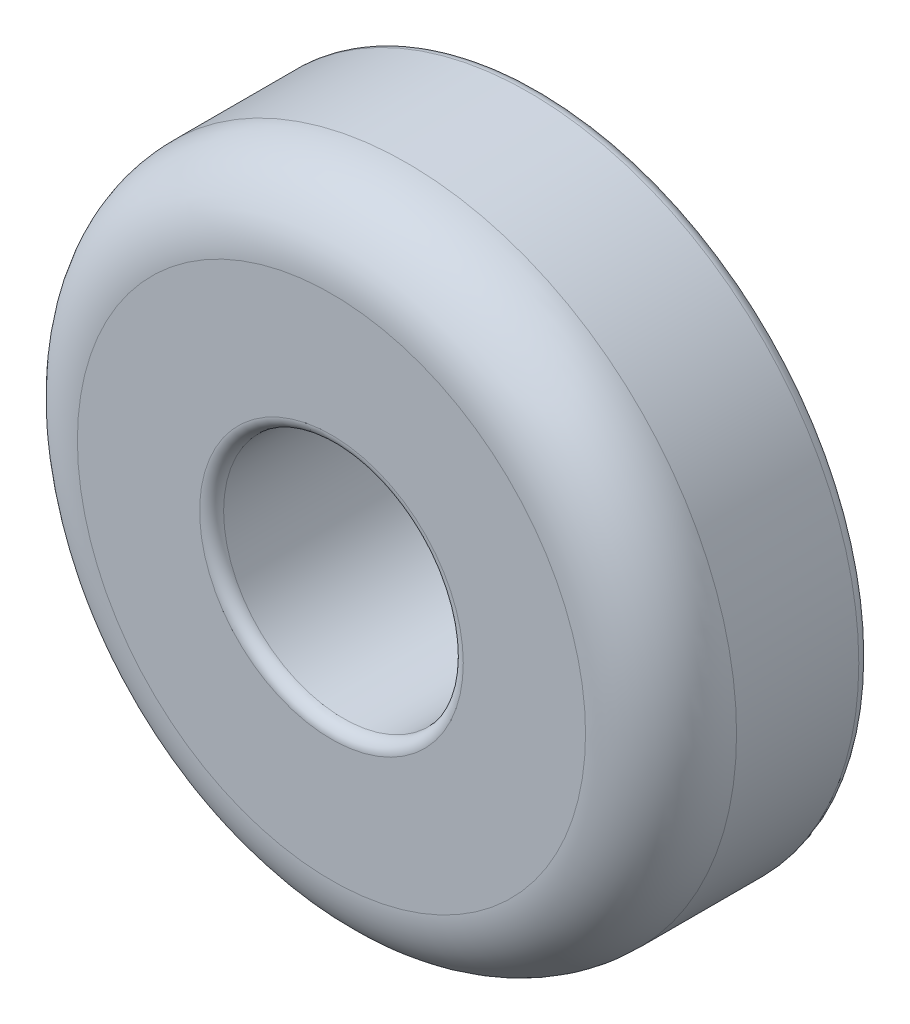
SolidWorks part; units mm, degrees
ref_plane "Front Plane" through (0, 0, 0) normal (0, 0, 1) x (1, 0, 0)
ref_plane "Top Plane" through (0, 0, 0) normal (0, 1, 0) x (1, 0, 0)
ref_plane "Right Plane" through (0, 0, 0) normal (1, 0, 0) x (0, 0, -1)
sketch "Sketch1" plane through (0, 0, 0) normal (0, 0, 1) x (1, 0, 0)
  circle A0 centre (0, 0) radius 1
  dimension "D1" = 2
extrude "Extrude-Thin1" add sketch "Sketch1" along normal blind 1.75 thin
fillet "Fillet1" radius 0.1 3 edges at (1, 0, 0) (2.75, 0, 0) (1, 0, 1.75)
fillet "Fillet2" radius 0.63 1 edges at (2.75, 0, 1.75)
